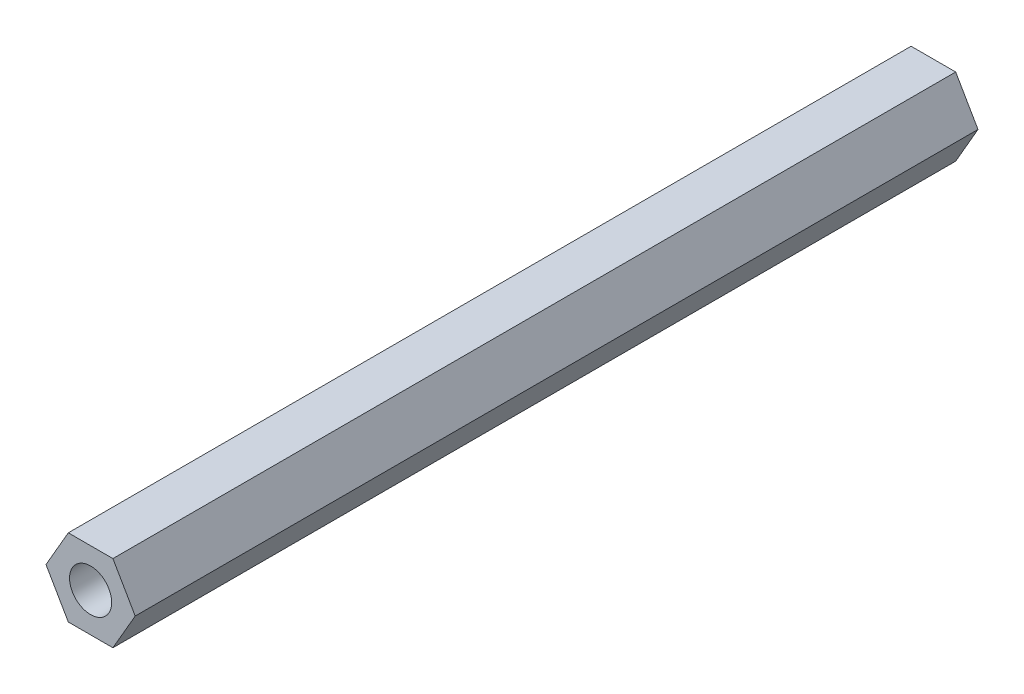
SolidWorks part; units mm, degrees
ref_plane "Front Plane" through (0, 0, 0) normal (0, 0, 1) x (1, 0, 0)
ref_plane "Top Plane" through (0, 0, 0) normal (0, 1, 0) x (1, 0, 0)
ref_plane "Right Plane" through (0, 0, 0) normal (1, 0, 0) x (0, 0, -1)
sketch "Sketch1" plane through (0, 0, 0) normal (0, 0, 1) x (1, 0, 0)
  line L1 (3.1754, 0) -> (1.5877, 2.75)
  line L2 (1.5877, 2.75) -> (-1.5877, 2.75)
  line L3 (-1.5877, 2.75) -> (-3.1754, 0)
  line L4 (-3.1754, 0) -> (-1.5877, -2.75)
  line L5 (-1.5877, -2.75) -> (1.5877, -2.75)
  line L6 (1.5877, -2.75) -> (3.1754, 0)
  circle A0 centre (0, 0) radius 1.5
  circle A1 centre (0, 0) radius 2.75 construction
  dimension "D2" = 3
  dimension "D1" = 5.5
extrude "Boss-Extrude1" add sketch "Sketch1" along normal blind 60
